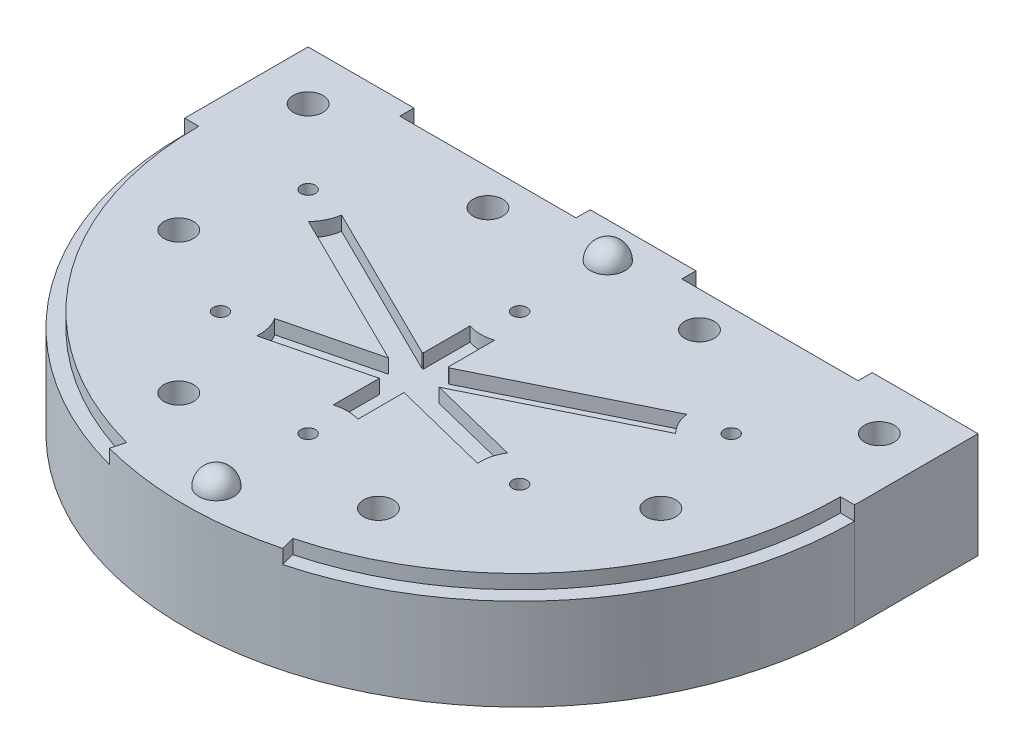
SolidWorks part; units mm, degrees
ref_plane "Front Plane" through (0, 0, 0) normal (0, 0, 1) x (1, 0, 0)
ref_plane "Top Plane" through (0, 0, 0) normal (0, 1, 0) x (1, 0, 0)
ref_plane "Right Plane" through (0, 0, 0) normal (1, 0, 0) x (0, 0, -1)
sketch "Sketch1" plane through (0, 0, 0) normal (0, 1, 0) x (1, 0, 0)
  line L0 (-30, 0) -> (30, 0) construction
  line L1 (-47.5, 17.5) -> (47.5, 17.5)
  line L2 (-47.5, 17.5) -> (-47.5, 0)
  line L4 (47.5, 17.5) -> (47.5, 0)
  line L5 (-47.5, 17.5) -> (44.5713, -16.421) construction
  line L6 (-44.5713, -16.421) -> (47.5, 17.5) construction
  line L7 (0, 0) -> (21.2132, -21.2132) construction
  line L8 (21.2132, -21.2132) -> (0, 0) construction
  line L9 (0, 0) -> (-21.2132, -21.2132) construction
  arc A8 (-30, 0) -> (30, 0) centre (0, 0) ccw construction
  circle A9 centre (-30, 0) radius 7.5 construction
  circle A10 centre (30, 0) radius 7.5 construction
  circle A11 centre (0, 0) radius 7.5 construction
  circle A12 centre (0, -30) radius 7.5 construction
  circle A13 centre (-21.2132, -21.2132) radius 7.5 construction
  circle A14 centre (21.2132, -21.2132) radius 7.5 construction
  arc A15 (-47.5, 0) -> (0, -47.5) centre (0, 0) ccw
  arc A16 (0, -47.5) -> (47.5, 0) centre (0, 0) ccw
  point P0 (0, 0)
  point P19 (0, -37.5)
  point P20 (37.5, 0)
  point P21 (0, 7.5)
  point P23 (-37.5, 0)
  dimension "D1" = 15
  dimension "D2" = 45
  dimension "D7" = 30
  dimension "D3" = 45
  dimension "D4" = 10
  dimension "D5" = 10
  dimension "D6" = 10
extrude "Boss-Extrude1" add sketch "Sketch1" along normal blind 15
ref_plane "Plane1" through (0, 0, 0) normal (0, 0, -1) x (-1, 0, 0)
sketch "Sketch2" plane through (0, 15, 0) normal (0, 1, 0) x (1, 0, 0)
  line L0 (13.7136, -21.1399) -> (1.75, -18.1451)
  line L1 (-1.75, -7.293) -> (-1.75, -11.8549)
  line L2 (3.5992, -15) -> (14.5635, -17.7446)
  line L3 (-1.75, -18.1451) -> (-1.75, -22.707)
  line L4 (1.75, -7.293) -> (1.75, -11.8549)
  line L5 (-1.75, -7.293) -> (1.75, -7.293) construction
  line L6 (0, -7.5) -> (0, -22.5) construction
  line L7 (-1.75, -22.707) -> (1.75, -22.707) construction
  line L8 (1.75, -22.707) -> (1.75, -18.1451)
  line L9 (14.5635, -17.7446) -> (13.7136, -21.1399) construction
  line L10 (1.8932, -11.939) -> (22.6866, -1.6624)
  line L11 (22.6866, -1.6624) -> (24.2373, -4.8001) construction
  line L12 (24.2373, -4.8001) -> (3.5992, -15)
  line L13 (1.75, -11.8549) -> (1.8932, -11.939)
  line L14 (-1.75, -11.8549) -> (-1.8932, -11.939)
  line L15 (-13.7136, -21.1399) -> (-1.75, -18.1451)
  line L16 (-14.5635, -17.7446) -> (-13.7136, -21.1399) construction
  line L17 (-3.5992, -15) -> (-14.5635, -17.7446)
  line L18 (-22.6866, -1.6624) -> (-24.2373, -4.8001) construction
  line L19 (-24.2373, -4.8001) -> (-3.5992, -15)
  line L20 (-1.8932, -11.939) -> (-22.6866, -1.6624)
  line L21 (-22.6866, -1.6624) -> (-24.4795, -0.7763)
  line L22 (-14.5635, -17.7446) -> (-16.5036, -18.2303)
  line L23 (-26.0303, -3.914) -> (-24.2373, -4.8001)
  line L24 (-13.7136, -21.1399) -> (-15.6537, -21.6255)
  line L25 (-1.75, -22.707) -> (-1.75, -24.707)
  line L26 (1.75, -22.707) -> (1.75, -24.707)
  line L27 (-1.75, -7.293) -> (-1.75, -5.293)
  line L28 (1.75, -7.293) -> (1.75, -5.293)
  line L29 (13.7136, -21.1399) -> (15.6537, -21.6255)
  line L30 (14.5635, -17.7446) -> (16.5036, -18.2303)
  line L31 (26.0303, -3.914) -> (24.2373, -4.8001)
  line L32 (22.6866, -1.6624) -> (24.4795, -0.7763)
  circle A0 centre (-21.2132, -21.2132) radius 7.5 construction
  circle A1 centre (0, -30) radius 7.5 construction
  circle A2 centre (21.2132, -21.2132) radius 7.5 construction
  circle A3 centre (30, 0) radius 7.5 construction
  circle A4 centre (0, 0) radius 7.5 construction
  circle A5 centre (-30, 0) radius 7.5 construction
  circle A6 centre (-21.2132, -21.2132) radius 7.5 construction
  circle A7 centre (0, -30) radius 7.5 construction
  circle A8 centre (21.2132, -21.2132) radius 7.5 construction
  circle A9 centre (30, 0) radius 7.5 construction
  circle A10 centre (0, 0) radius 7.5 construction
  circle A11 centre (-30, 0) radius 7.5 construction
  arc A12 (-1.75, -11.8549) -> (-1.75, -18.1451) centre (0, -15) ccw construction
  arc A13 (1.75, -18.1451) -> (1.75, -11.8549) centre (0, -15) ccw construction
  arc A14 (-26.0303, -3.914) -> (-24.4795, -0.7763) centre (-30, 0) ccw
  arc A15 (-16.5036, -18.2303) -> (-15.6537, -21.6255) centre (-21.2132, -21.2132) cw
  arc A16 (-1.75, -24.707) -> (1.75, -24.707) centre (0, -30) cw
  arc A17 (-1.75, -5.293) -> (1.75, -5.293) centre (0, 0) ccw
  arc A18 (16.5036, -18.2303) -> (15.6537, -21.6255) centre (21.2132, -21.2132) ccw
  arc A19 (26.0303, -3.914) -> (24.4795, -0.7763) centre (30, 0) cw
  point P2 (0, -7.5)
  point P3 (0, -22.5)
  point P45 (3.5992, -15)
  dimension "D1" = 2
  dimension "D5" = 2
  dimension "D7" = 2
  dimension "D2" = 3.5
  dimension "D3" = 3.5
  dimension "D4" = 3.5
  dimension "D6" = 2
extrude "Cut-Extrude1" cut sketch "Sketch2" against normal blind 2
hole_wizard "M2.5x0.45 Tapped Hole1" positions "Sketch7" profile "Sketch8" tap size "M2.5x0.45" standard "ANSI Metric" end condition through all
sketch "Sketch7" plane through (0, 15, 0) normal (0, 1, 0) x (1, 0, 0)
  circle A0 centre (-30, 0) radius 7.5 construction
  circle A1 centre (30, 0) radius 7.5 construction
  circle A2 centre (21.2132, -21.2132) radius 7.5 construction
  circle A3 centre (0, -30) radius 7.5 construction
  circle A4 centre (-21.2132, -21.2132) radius 7.5 construction
  point P0 (-30, 0)
  point P2 (0, 0)
  point P5 (30, 0)
  point P7 (21.2132, -21.2132)
  point P9 (0, -30)
  point P11 (-21.2132, -21.2132)
sketch "Sketch8" plane through (-30, 15, 0) normal (1, 0, 0) x (0, 0, 1)
  line L0 (0, 0) -> (0, 15)
  line L1 (0, 15) -> (1.025, 15)
  line L2 (1.025, 15) -> (1.025, 0)
  line L5 (1.025, 0) -> (0, 0)
  line L11 (0, -6.35) -> (0, 107.95) construction
  dimension "Thru Tap Drill Dia." = 2.05
  dimension "Thru Tap Drill Depth" = 15
cosmetic thread "Hole Thread1" parameters "D2"=2.5
cosmetic thread "Hole Thread2" parameters "D2"=2.5
cosmetic thread "Hole Thread3" parameters "D2"=2.5
cosmetic thread "Hole Thread4" parameters "D2"=2.5
cosmetic thread "Hole Thread5" parameters "D2"=2.5
cosmetic thread "Hole Thread6" parameters "D2"=2.5
sketch "Sketch9" plane through (0, 15, 0) normal (0, 1, 0) x (1, 0, 0)
  line L0 (47.5, 17.5) -> (-47.5, 17.5) construction
  line L1 (-32.5, 17.5) -> (-7.5, 17.5)
  line L2 (-32.5, 17.5) -> (-32.5, 15.5)
  line L3 (-32.5, 15.5) -> (-7.5, 15.5)
  line L4 (32.5, 17.5) -> (32.5, 15.5)
  line L5 (11.7763, -43.9496) -> (12.2939, -45.8815)
  line L6 (-47.5, 0) -> (-45.5, 0)
  line L7 (47.5, 0) -> (45.5, 0)
  line L8 (-11.7763, -43.9496) -> (-12.2939, -45.8815)
  line L9 (1.75, -24.707) -> (1.75, -18.1451) construction
  line L10 (-1.75, -18.1451) -> (-1.75, -24.707) construction
  line L11 (7.5, 15.5) -> (7.5, 17.5)
  line L12 (-7.5, 15.5) -> (-7.5, 17.5)
  line L13 (7.5, 15.5) -> (32.5, 15.5)
  line L14 (7.5, 17.5) -> (32.5, 17.5)
  line L15 (-7.5, 16.5) -> (7.5, 16.5) construction
  arc A0 (-47.5, 0) -> (0, -47.5) centre (0, 0) ccw construction
  arc A1 (-47.5, 0) -> (-12.2939, -45.8815) centre (0, 0) ccw
  arc A2 (0, -47.5) -> (47.5, 0) centre (0, 0) ccw construction
  arc A3 (12.2939, -45.8815) -> (47.5, 0) centre (0, 0) ccw
  arc A4 (-45.5, 0) -> (-11.7763, -43.9496) centre (0, 0) ccw
  arc A5 (11.7763, -43.9496) -> (45.5, 0) centre (0, 0) ccw
  point P27 (0, 16.5)
  point P29 (7.5, 16.5)
  dimension "D3" = 2
  dimension "D1" = 2
  dimension "D2" = 65
  dimension "D4" = 15
  dimension "D5" = 15
  dimension "D6" = 15
extrude "Cut-Extrude2" cut sketch "Sketch9" against normal blind 2
hole_wizard "M5x0.8 Tapped Hole1" positions "Sketch10" profile "Sketch11" tap size "M5x0.8" standard "ANSI Metric" end condition through all
sketch "Sketch10" plane through (0, 15, 0) normal (0, 1, 0) x (1, 0, 0)
  line L0 (0, 0) -> (-34.1835, -14.1593) construction
  line L2 (0, 0) -> (-14.1593, -34.1835) construction
  line L4 (14.1593, -34.1835) -> (0, 0) construction
  line L6 (0, 0) -> (34.1835, -14.1593) construction
  line L8 (-47.5, 17.5) -> (47.5, 17.5) construction
  line L9 (-47.5, 17.5) -> (-47.5, 0) construction
  line L10 (47.5, 17.5) -> (47.5, 0) construction
  line L11 (-30, 0) -> (30, 0) construction
  line L12 (-40.5, 10.5) -> (40.5, 10.5) construction
  arc A0 (-37, 0) -> (37, 0) centre (0, 0) ccw
  point P0 (-40.5, 10.5)
  point P2 (-34.1835, -14.1593)
  point P4 (34.1835, -14.1593)
  point P6 (-14.1593, -34.1835)
  point P8 (14.1593, -34.1835)
  point P11 (40.5, 10.5)
  point P59 (-15, 10.5)
  point P61 (15, 10.5)
  dimension "D4" = 37
  dimension "D1" = 7
  dimension "D2" = 7
  dimension "D3" = 7
  dimension "D5" = 22.5
  dimension "D6" = 45
  dimension "D7" = 22.5
  dimension "D8" = 45
  dimension "D9" = 15
  dimension "D10" = 15
sketch "Sketch11" plane through (-40.5, 15, -10.5) normal (1, 0, 0) x (0, 0, 1)
  line L0 (0, 0) -> (0, 15)
  line L1 (0, 15) -> (2.1, 15)
  line L2 (2.1, 15) -> (2.1, 0)
  line L5 (2.1, 0) -> (0, 0)
  line L11 (0, -6.35) -> (0, 107.95) construction
  dimension "Thru Tap Drill Dia." = 4.2
  dimension "Thru Tap Drill Depth" = 15
cosmetic thread "Hole Thread7" parameters "D2"=5
cosmetic thread "Hole Thread8" parameters "D2"=5
cosmetic thread "Hole Thread9" parameters "D2"=5
cosmetic thread "Hole Thread10" parameters "D2"=5
cosmetic thread "Hole Thread11" parameters "D2"=5
cosmetic thread "Hole Thread12" parameters "D2"=5
cosmetic thread "Hole Thread13" parameters "D2"=5
cosmetic thread "Hole Thread14" parameters "D2"=5
sketch "Sketch15" plane through (0, 0, 0) normal (1, 0, 0) x (0, 0, -1)
  line L0 (-43, 15) -> (-40.5, 15) construction
  line L1 (-43, 15) -> (-43, 17.5) construction
  line L2 (12.6, 15) -> (8.4, 15) construction
  line L3 (-43, 17.4746) -> (-43, 15)
  line L4 (-43, 15) -> (-40.5254, 15)
  arc A0 (-43, 17.5) -> (-40.5, 15) centre (-43, 15) cw construction
  arc A1 (-43, 17.4746) -> (-40.5254, 15) centre (-43, 15) cw
  dimension "D1" = 2.5
  dimension "D2" = 4.5
  dimension "D3" = 0.0254
revolve "Revolve2" add sketch "Sketch15" angle 360 about L1
sketch "Sketch17" plane through (0, 0, 0) normal (1, 0, 0) x (0, 0, -1)
  line L0 (12.5, 15) -> (15, 15) construction
  line L1 (12.5, 15) -> (12.5, 17.5) construction
  line L2 (-40.5254, 15) -> (-45.4746, 15) construction
  line L3 (14.9746, 15) -> (12.5, 15)
  line L4 (12.5, 15) -> (12.5, 17.4746)
  arc A0 (12.5, 17.5) -> (15, 15) centre (12.5, 15) cw construction
  arc A1 (12.5, 17.4746) -> (14.9746, 15) centre (12.5, 15) cw
  dimension "D1" = 2.5
  dimension "D2" = 2.5
  dimension "D3" = 0.0254
revolve "Revolve3" add sketch "Sketch17" angle 360 about L1
